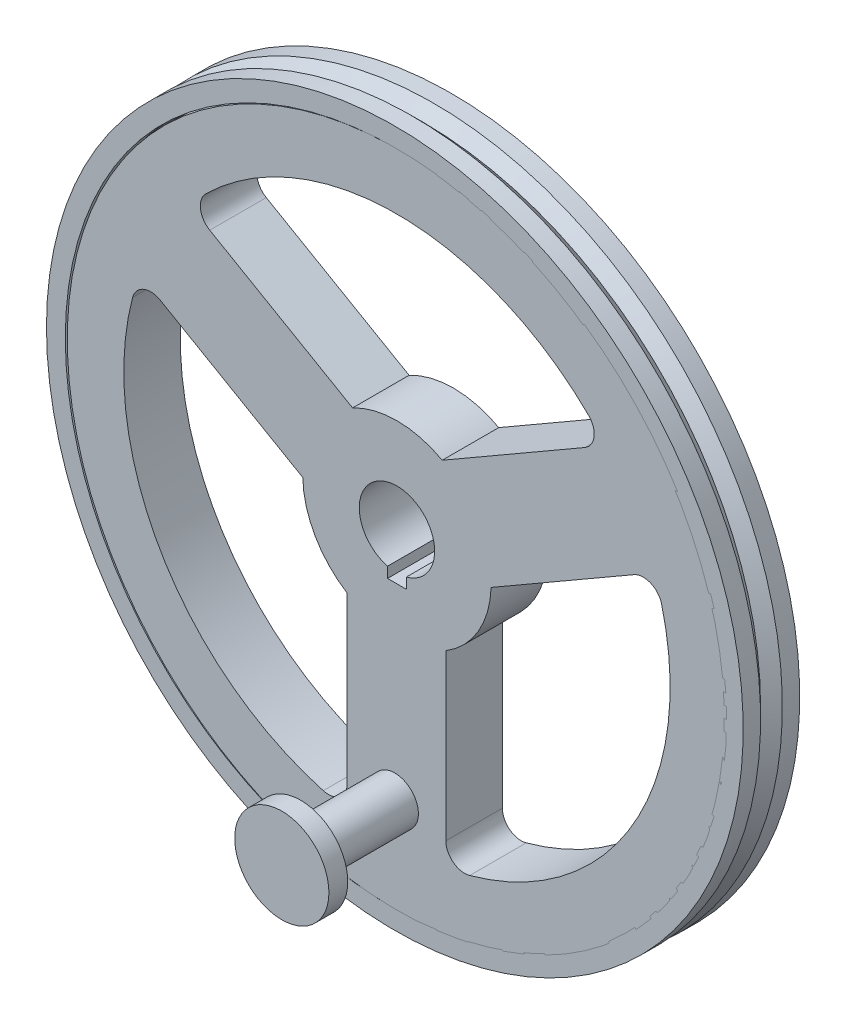
SolidWorks part; units mm, degrees
ref_plane "Front Plane" through (0, 0, 0) normal (0, 0, 1) x (1, 0, 0)
ref_plane "Top Plane" through (0, 0, 0) normal (0, 1, 0) x (1, 0, 0)
ref_plane "Right Plane" through (0, 0, 0) normal (1, 0, 0) x (0, 0, -1)
sketch "Sketch1" plane through (0, 0, 0) normal (0, 0, 1) x (1, 0, 0)
  line L0 (-97.6991, 0) -> (99.9482, 0) construction
  line L1 (1.1247, 196.531) -> (1.1247, -196.5918) construction
  line L2 (-25.2945, -129.9948) -> (-25.2945, -42.4504)
  line L3 (-98.2447, 87.877) -> (-22.429, 44.1048)
  line L4 (27.075, -42.7385) -> (27.075, -130.1252)
  line L5 (-48.8632, -1.1045) -> (-124.5424, 42.5889)
  line L6 (126.9129, 42.1178) -> (51.0972, -1.6544)
  line L7 (25.162, 43.843) -> (100.8411, 87.5363)
  line L9 (6.1246, -15) -> (-3.8754, -15)
  line L10 (6.1246, -15) -> (6.1246, -25)
  line L11 (6.1246, -25) -> (-3.8754, -25)
  line L12 (-3.8754, -15) -> (-3.8754, -25)
  line L13 (6.1246, -15) -> (-3.8754, -25) construction
  line L14 (6.1246, -25) -> (-3.8754, -15) construction
  arc A0 (-48.8754, 0) -> (-25.2945, -42.4504) centre (1.1246, 0) ccw
  circle A1 centre (1.1246, 0) radius 20
  circle A2 centre (1.1246, 0) radius 175
  arc A3 (39.738, -139.7641) -> (141.6009, 35.9359) centre (1.1246, 0) ccw
  arc A5 (39.738, -139.7641) -> (141.6009, 35.9359) centre (1.1246, 0) ccw
  arc A6 (-139.2214, 36.4419) -> (-37.9922, -139.6241) centre (1.1246, 0) ccw
  arc A7 (102.8571, 103.3222) -> (-100.235, 103.6881) centre (1.1246, 0) ccw
  arc A8 (25.162, 43.843) -> (-22.429, 44.1048) centre (1.1246, 0) ccw
  arc A9 (27.075, -42.7385) -> (51.0972, -1.6544) centre (1.1246, 0) ccw
  arc A10 (-139.2214, 36.4419) -> (-37.9922, -139.6241) centre (1.1246, 0) ccw
  arc A11 (102.8571, 103.3222) -> (-100.235, 103.6881) centre (1.1246, 0) ccw
  arc A12 (100.8411, 87.5363) -> (102.8571, 103.3222) centre (95.8411, 96.1966) ccw
  arc A13 (-25.2945, -129.9948) -> (-37.9922, -139.6241) centre (-35.2945, -129.9948) cw
  arc A14 (-139.2214, 36.4419) -> (-124.5424, 42.5889) centre (-129.5424, 33.9286) cw
  arc A15 (-100.235, 103.6881) -> (-98.2447, 87.877) centre (-93.2447, 96.5372) ccw
  arc A16 (27.075, -130.1252) -> (39.738, -139.7641) centre (37.075, -130.1252) ccw
  arc A17 (126.9129, 42.1178) -> (141.6009, 35.9359) centre (131.9129, 33.4576) cw
  point P10 (1.1246, -25)
  point P28 (1.1246, 0)
  point P33 (1.1246, -20)
  dimension "D1" = 40
  dimension "D2" = 100
  dimension "D3" = 290
  dimension "D4" = 350
  dimension "D5" = 5
  dimension "D8" = 10
  dimension "D6" = 3
  dimension "D7" = 10
extrude "Boss-Extrude1" add sketch "Sketch1" along normal blind 30
sketch "Sketch2" plane through (0, 0, 30) normal (0, 0, 1) x (1, 0, 0)
  circle A0 centre (0, -125) radius 12.5
  dimension "D1" = 25
  dimension "D2" = 125
extrude "Boss-Extrude2" add sketch "Sketch2" along normal blind 50
sketch "Sketch3" plane through (0, 0, 80) normal (0, 0, 1) x (1, 0, 0)
  circle A0 centre (0, -125) radius 25
  dimension "50" = 50
extrude "Boss-Extrude3" add sketch "Sketch3" along normal blind 10
ref_plane "Plane1" through (0, 0, 0) normal (1, 0, 0) x (0, 0, -1)
sketch "Sketch5" plane through (0, 0, 0) normal (1, 0, 0) x (0, 0, -1)
  line L1 (-30, 175) -> (-30, -175) construction
  line L3 (-5.0778, 174.9222) -> (0, 174.9222)
  line L4 (0, -175) -> (0, 175) construction
  line L6 (0, 175) -> (-30, 175) construction
  line L7 (-5.0778, 174.9222) -> (-15, 165)
  line L10 (-24.9222, 174.9222) -> (-15, 165)
  line L11 (0, 0) -> (-45.9332, 0) construction
  line L12 (-30, 174.9222) -> (-24.9222, 174.9222)
  point P18 (0, 161.4348)
  point P21 (-30, 161.4348)
  dimension "D3" = 10
revolve "Revolve-Thin11" add sketch "Sketch5" angle 360 about L11 wall 10
